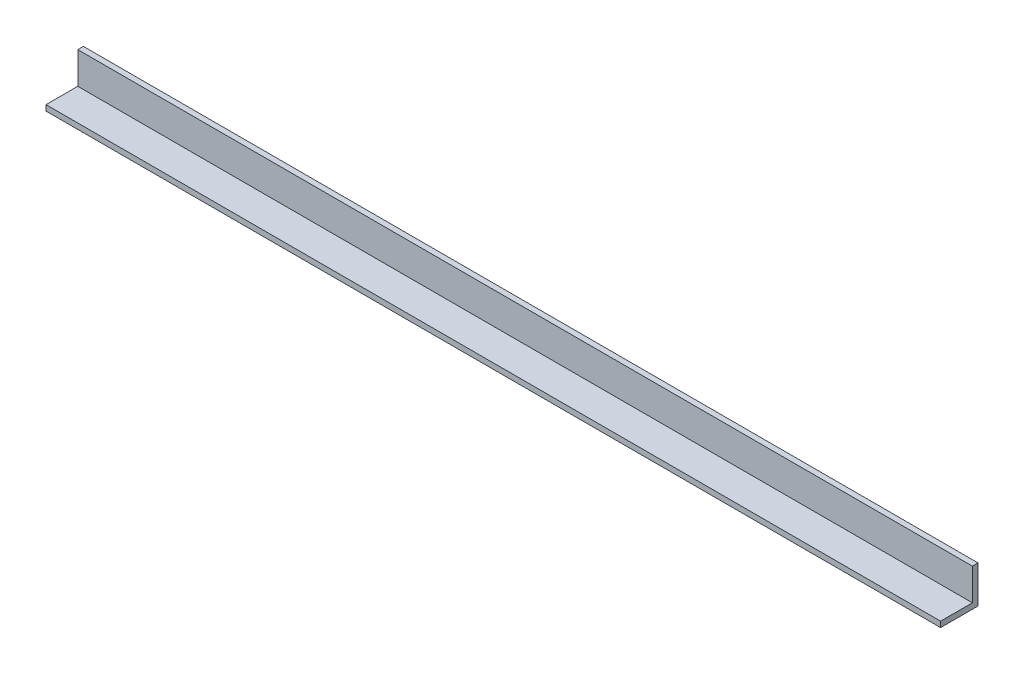
SolidWorks part; units mm, degrees
ref_plane "前视基准面" through (0, 0, 0) normal (0, 0, 1) x (1, 0, 0)
ref_plane "上视基准面" through (0, 0, 0) normal (0, 1, 0) x (1, 0, 0)
ref_plane "右视基准面" through (0, 0, 0) normal (1, 0, 0) x (0, 0, -1)
sketch "草图1" plane through (0, 0, 0) normal (0, 0, 1) x (1, 0, 0)
  line L1 (0, 0) -> (1915, 0)
  line L2 (0, 0) -> (0, 80)
  line L3 (0, 80) -> (1915, 80)
  line L4 (1915, 0) -> (1915, 80)
  dimension "D1" = 1915
  dimension "D2" = 80
extrude "拉伸1" add sketch "草图1" along normal blind 80
sketch "草图3" plane through (0, 0, 0) normal (-1, 0, 0) x (0, 0, 1)
  line L0 (80, 80) -> (80, 0) construction
  line L1 (12, 80) -> (80, 80)
  line L2 (12, 80) -> (12, 12)
  line L3 (12, 12) -> (80, 12)
  line L4 (80, 80) -> (80, 12)
  line L5 (80, 80) -> (0, 80) construction
  line L6 (80, 0) -> (0, 0) construction
  line L7 (0, 80) -> (0, 0) construction
  dimension "D1" = 12
  dimension "D2" = 12
extrude "拉伸2" cut sketch "草图3" against normal through all
